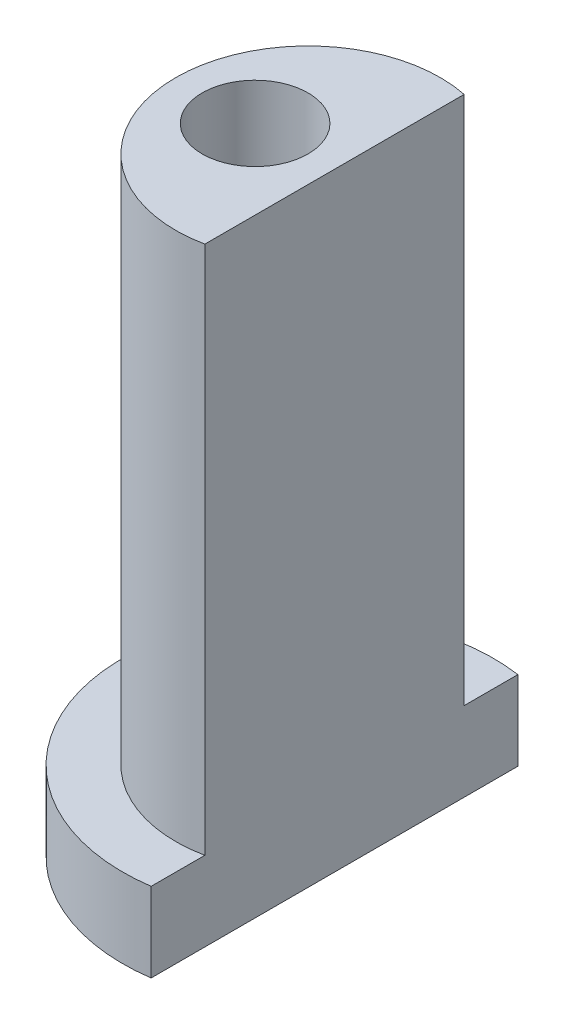
SolidWorks part; units mm, degrees
ref_plane "前视基准面" through (0, 0, 0) normal (0, 0, 1) x (1, 0, 0)
ref_plane "上视基准面" through (0, 0, 0) normal (0, 1, 0) x (1, 0, 0)
ref_plane "右视基准面" through (0, 0, 0) normal (1, 0, 0) x (0, 0, -1)
sketch "草图1" plane through (0, 0, 0) normal (0, 1, 0) x (1, 0, 0)
  circle A0 centre (0, 0) radius 7
  dimension "D1" = 14
extrude "凸台-拉伸1" add sketch "草图1" along normal blind 3
sketch "草图2" plane through (0, 3, 0) normal (0, 1, 0) x (1, 0, 0)
  circle A0 centre (0, 0) radius 5
  dimension "D1" = 10
extrude "凸台-拉伸2" add sketch "草图2" along normal blind 20
sketch "草图3" plane through (0, 23, 0) normal (0, 1, 0) x (1, 0, 0)
  line L0 (-5, 0) -> (5, 0) construction
  circle A0 centre (-2, 0) radius 2
  circle A1 centre (0, 0) radius 5 construction
  circle A2 centre (0, 0) radius 5 construction
  point P10 (-1.3416, 0)
  dimension "D1" = 4
  dimension "D2" = 2
extrude "切除-拉伸1" cut sketch "草图3" against normal through all
sketch "草图4" plane through (0, 23, 0) normal (0, 1, 0) x (1, 0, 0)
  line L1 (1, 6.9282) -> (9.6161, 6.9282)
  line L2 (1, 6.9282) -> (1, -7.1125)
  line L3 (1, -7.1125) -> (9.6161, -7.1125)
  line L4 (9.6161, 6.9282) -> (9.6161, -7.1125)
  circle A0 centre (0, 0) radius 7 construction
  dimension "D1" = 1
extrude "切除-拉伸2" cut sketch "草图4" against normal through all
